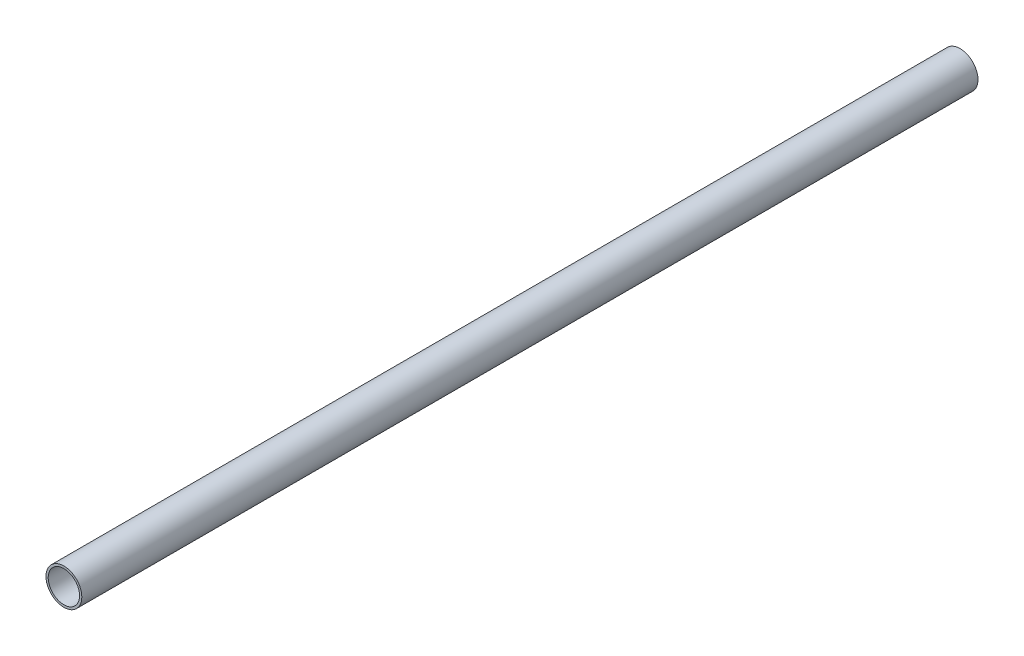
SolidWorks part; units mm, degrees
material "Hexcel AS4C (3000 filamentos)"
ref_plane "Alzado" through (0, 0, 0) normal (0, 0, 1) x (1, 0, 0)
ref_plane "Planta" through (0, 0, 0) normal (0, 1, 0) x (1, 0, 0)
ref_plane "Vista lateral" through (0, 0, 0) normal (1, 0, 0) x (0, 0, -1)
sketch "Croquis1" plane through (0, 0, 0) normal (0, 0, 1) x (1, 0, 0)
  circle A0 centre (0, 0) radius 8
  circle A1 centre (0, 0) radius 7
  dimension "D1" = 16
  dimension "D2" = 14
extrude "Saliente-Extruir1" add sketch "Croquis1" along normal mid plane 400
